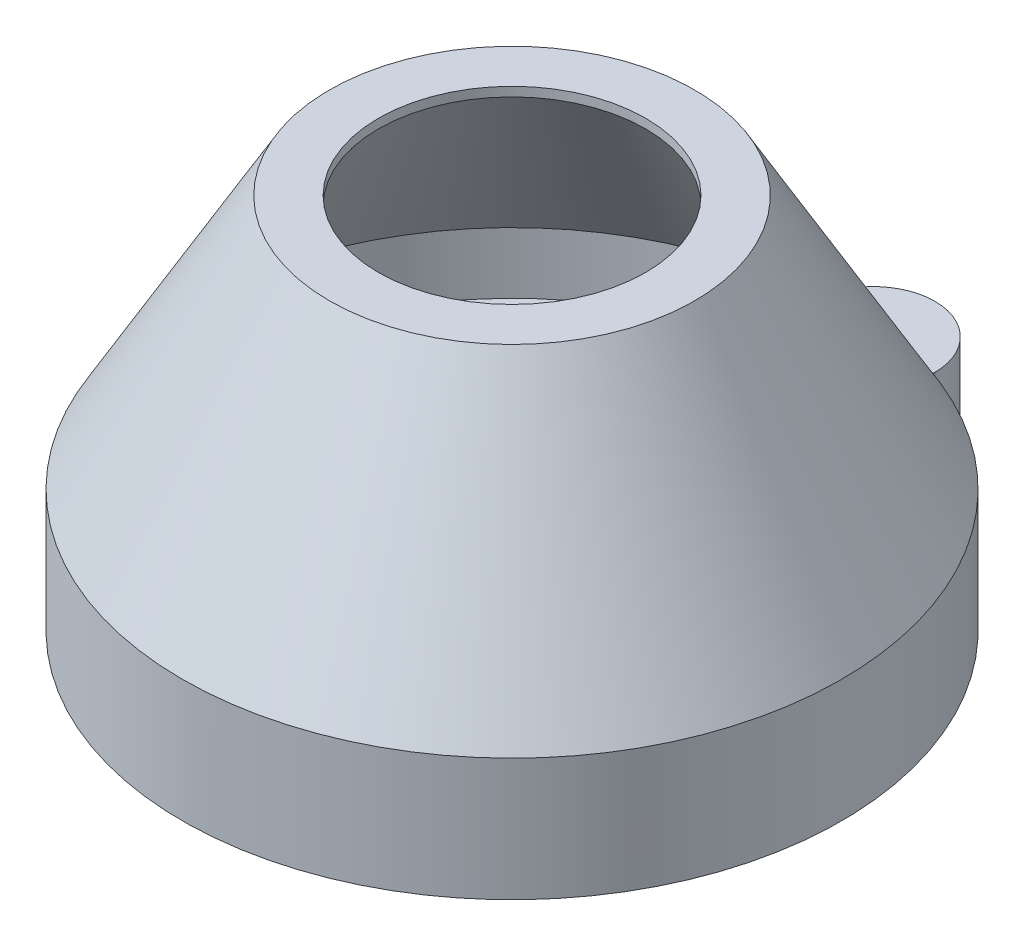
SolidWorks part; units mm, degrees
ref_plane "Front Plane" through (0, 0, 0) normal (0, 0, 1) x (1, 0, 0)
ref_plane "Top Plane" through (0, 0, 0) normal (0, 1, 0) x (1, 0, 0)
ref_plane "Right Plane" through (0, 0, 0) normal (1, 0, 0) x (0, 0, -1)
sketch "Sketch3" plane through (0, 0, 0) normal (0, 1, 0) x (1, 0, 0)
  circle A0 centre (0, 0) radius 26.128
  circle A1 centre (0, 0) radius 26.878
extrude "Boss-Extrude1" add sketch "Sketch3" along normal blind 10
sketch "Sketch4" plane through (0, 10, 0) normal (0, 1, 0) x (1, 0, 0)
  circle A0 centre (0, 0) radius 26.878
sketch "Sketch5" plane through (0, 0, 0) normal (0, -1, 0) x (1, 0, 0)
  line L0 (-5.5432, -29.9954) -> (-5.5432, -26.3002)
  line L1 (4.4919, -29.9954) -> (4.4919, -26.5)
  arc A0 (-5.5432, -29.9954) -> (4.4919, -29.9954) centre (-0.5256, -29.9954) ccw
  circle A1 centre (0, 0) radius 26.878 construction
  arc A2 (-5.5432, -26.3002) -> (4.4919, -26.5) centre (0.0111, 0.5595) ccw
  circle A3 centre (-0.5256, -29.9954) radius 1.5
  dimension "D1" = 30
extrude "Boss-Extrude4" add sketch "Sketch5" against normal blind 5.5
sketch "Sketch6" plane through (0, 0, 0) normal (0, -1, 0) x (-1, 0, 0)
  line L0 (4.7101, 29.9954) -> (4.7101, 25.6999)
  line L1 (-3.6589, 29.9954) -> (-3.6589, 25.8176)
  arc A0 (4.7101, 29.9954) -> (-3.6589, 29.9954) centre (0.5256, 29.9954) ccw
  circle A1 centre (0, 0) radius 26.128 construction
  arc A3 (4.7101, 25.6999) -> (-3.6589, 25.8176) centre (0.1631, -0.0266) ccw
extrude "Cut-Extrude1" cut sketch "Sketch6" against normal blind 3.5
ref_axis "Center" through (0, 30.1875, 0) along (0, -1, 0)
sketch "Sketch7" plane through (0, 0, 0) normal (0, 0, 1) x (1, 0, 0)
  line L0 (-26.878, 10) -> (-14.898, 30.75)
  line L2 (-14.581, 30) -> (-26.128, 10)
  line L3 (-26.128, 10) -> (-26.878, 10)
  line L4 (26.128, 10) -> (-26.128, 10) construction
  line L5 (-14.581, 30) -> (-10.898, 30)
  line L6 (-10.898, 30) -> (-10.898, 30.75)
  line L7 (-10.898, 30.75) -> (-14.898, 30.75)
  dimension "D1" = 0.75
  dimension "D2" = 60
  dimension "D3" = 20
  dimension "D4" = 60
  dimension "D5" = 0
  dimension "D6" = 4
revolve "Revolve1" add sketch "Sketch7" angle 360 about axis through (0, 30.1875, 0) along (0, -1, 0)
sketch "Sketch8" plane through (0, 0, 0) normal (0, -1, 0) x (1, 0, 0)
  circle A0 centre (0, 0) radius 26.128
  circle A1 centre (0, 0) radius 25.5
extrude "Boss-Extrude5" add sketch "Sketch8" against normal blind 1.5 from offset 3.5 offset against normal yes
fillet "Fillet1" [suppressed] radius 2
